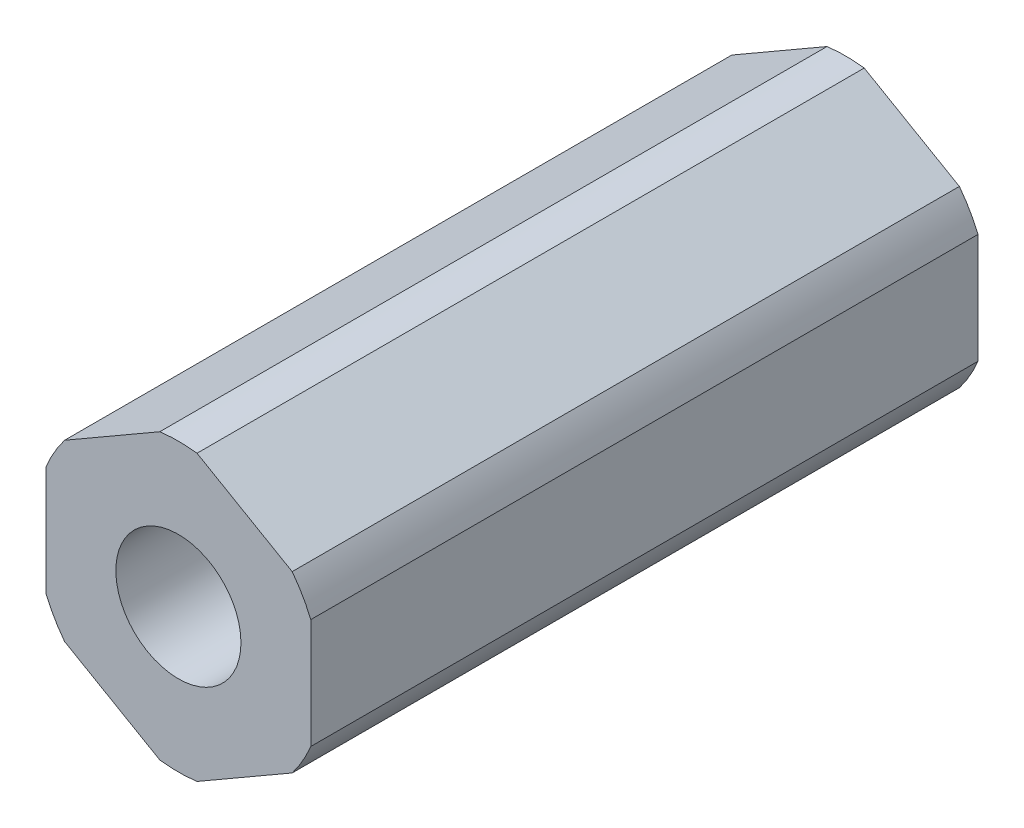
SolidWorks part; units mm, degrees
ref_plane "Front Plane" through (0, 0, 0) normal (0, 0, 1) x (1, 0, 0)
ref_plane "Top Plane" through (0, 0, 0) normal (0, 1, 0) x (1, 0, 0)
ref_plane "Right Plane" through (0, 0, 0) normal (1, 0, 0) x (0, 0, -1)
sketch "Sketch1" plane through (0, 0, 0) normal (0, 0, 1) x (1, 0, 0)
  line L0 (-6.35, 3.6662) -> (-6.35, 2.635) construction
  line L1 (-0.893, 6.8168) -> (-5.457, 4.1818)
  line L2 (-6.35, 2.635) -> (-6.35, -2.635)
  line L3 (-5.457, -4.1818) -> (-0.893, -6.8168)
  line L4 (0.893, -6.8168) -> (5.457, -4.1818)
  line L5 (6.35, -2.635) -> (6.35, 2.635)
  line L6 (5.457, 4.1818) -> (0.893, 6.8168)
  line L7 (-5.457, 4.1818) -> (-6.35, 3.6662) construction
  line L8 (0, 7.3323) -> (-0.893, 6.8168) construction
  line L9 (0.893, 6.8168) -> (0, 7.3323) construction
  line L10 (6.35, 3.6662) -> (5.457, 4.1818) construction
  line L11 (6.35, 2.635) -> (6.35, 3.6662) construction
  line L12 (6.35, -3.6662) -> (6.35, -2.635) construction
  line L13 (5.457, -4.1818) -> (6.35, -3.6662) construction
  line L14 (0, -7.3323) -> (0.893, -6.8168) construction
  line L15 (-0.893, -6.8168) -> (0, -7.3323) construction
  line L16 (-6.35, -3.6662) -> (-5.457, -4.1818) construction
  line L17 (-6.35, -2.635) -> (-6.35, -3.6662) construction
  circle A0 centre (0, 0) radius 6.35 construction
  circle A1 centre (0, 0) radius 3
  arc A2 (-5.457, 4.1818) -> (-6.35, 2.635) centre (0, 0) ccw
  arc A3 (0.893, 6.8168) -> (-0.893, 6.8168) centre (0, 0) ccw
  arc A4 (6.35, 2.635) -> (5.457, 4.1818) centre (0, 0) ccw
  arc A5 (5.457, -4.1818) -> (6.35, -2.635) centre (0, 0) ccw
  arc A6 (-0.893, -6.8168) -> (0.893, -6.8168) centre (0, 0) ccw
  arc A7 (-6.35, -2.635) -> (-5.457, -4.1818) centre (0, 0) ccw
  dimension "D2" = 6
  dimension "D3" = 13.75
  dimension "D1" = 12.7
extrude "Boss-Extrude1" add sketch "Sketch1" along normal mid plane 32
